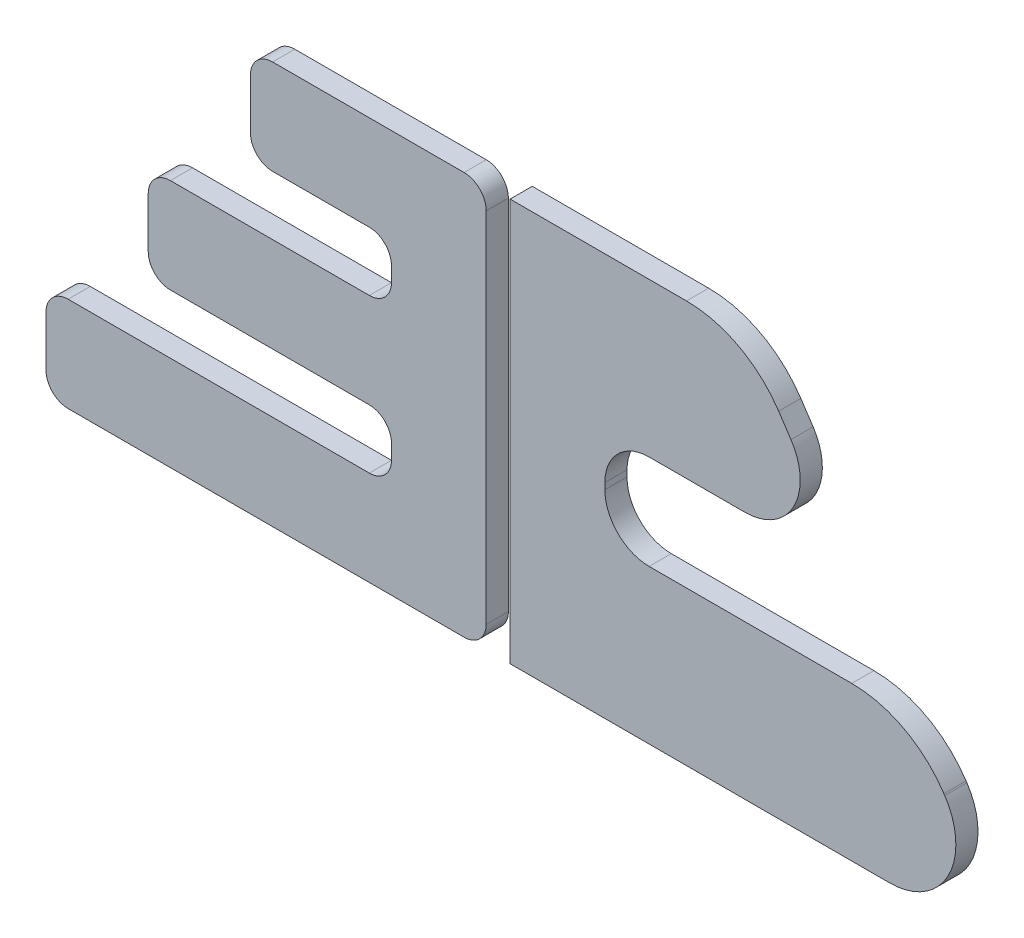
SolidWorks part; units mm, degrees
ref_plane "Plan de face" through (0, 0, 0) normal (0, 0, 1) x (1, 0, 0)
ref_plane "Plan de dessus" through (0, 0, 0) normal (0, 1, 0) x (1, 0, 0)
ref_plane "Plan de droite" through (0, 0, 0) normal (1, 0, 0) x (0, 0, -1)
sketch "Esquisse1" plane through (0, 0, 0) normal (0, 0, 1) x (1, 0, 0)
  line L0 (0, 181.7583) -> (0, 0)
  line L2 (-198.818, 0) -> (-198.818, 42.7982)
  line L3 (-198.818, 42.7982) -> (-42.7982, 42.7982)
  line L4 (-42.7982, 42.7982) -> (-42.7982, 69.48)
  line L5 (-42.7982, 69.48) -> (-152.6465, 69.48)
  line L6 (-152.6465, 69.48) -> (-152.6465, 112.2783)
  line L7 (-152.6465, 112.2783) -> (-42.7982, 112.2783)
  line L8 (-42.7982, 112.2783) -> (-42.7982, 138.9601)
  line L9 (-42.7982, 138.9601) -> (-106.4749, 138.9601)
  line L10 (-106.4749, 138.9601) -> (-106.4749, 181.7583)
  line L11 (-106.4749, 181.7583) -> (0, 181.7583)
  line L12 (-42.7982, 56.1391) -> (0, 56.1391) construction
  line L13 (-42.7982, 125.6192) -> (0, 125.6192) construction
  line L14 (-198.818, 42.7982) -> (-106.4749, 181.7583) construction
  line L15 (0, 0) -> (-198.818, 0)
  line L16 (10.782, 181.7583) -> (10.782, 0)
  line L17 (10.782, 0) -> (238.0626, 0)
  line L18 (238.0626, 0) -> (191.8827, 69.48)
  line L19 (117.257, 181.7583) -> (10.782, 181.7583)
  line L20 (53.5803, 112.2783) -> (163.4369, 112.2783)
  line L22 (191.8827, 69.48) -> (53.5803, 69.48)
  line L23 (53.5803, 69.48) -> (53.5803, 112.2783)
  line L24 (53.5803, 90.8791) -> (10.782, 90.8791) construction
  line L25 (163.4369, 112.2783) -> (117.257, 181.7583)
  dimension "D1" = 33.61
extrude "Boss.-Extru.1" add sketch "Esquisse1" along normal blind 10
fillet "Congé1" radius 10 12 edges at (0, 181.7583, 5) (0, 0, 5) (-198.818, 0, 5) (-198.818, 42.7982, 5) (-42.7982, 42.7982, 5) (-42.7982, 69.48, 5) (-152.6465, 69.48, 5) (-152.6465, 112.2783, 5) (-42.7982, 112.2783, 5) (-42.7982, 138.9601, 5) (-106.4749, 138.9601, 5) (-106.4749, 181.7583, 5)
fillet "Congé2" radius 25 1 edges at (163.4369, 112.2783, 5)
fillet "Congé3" radius 50 1 edges at (191.8827, 69.48, 5)
fillet "Congé4" radius 30 1 edges at (238.0626, 0, 5)
fillet "Congé5" radius 50 1 edges at (117.257, 181.7583, 5)
fillet "Congé6" radius 20 2 edges at (53.5803, 69.48, 5) (53.5803, 112.2783, 5)
